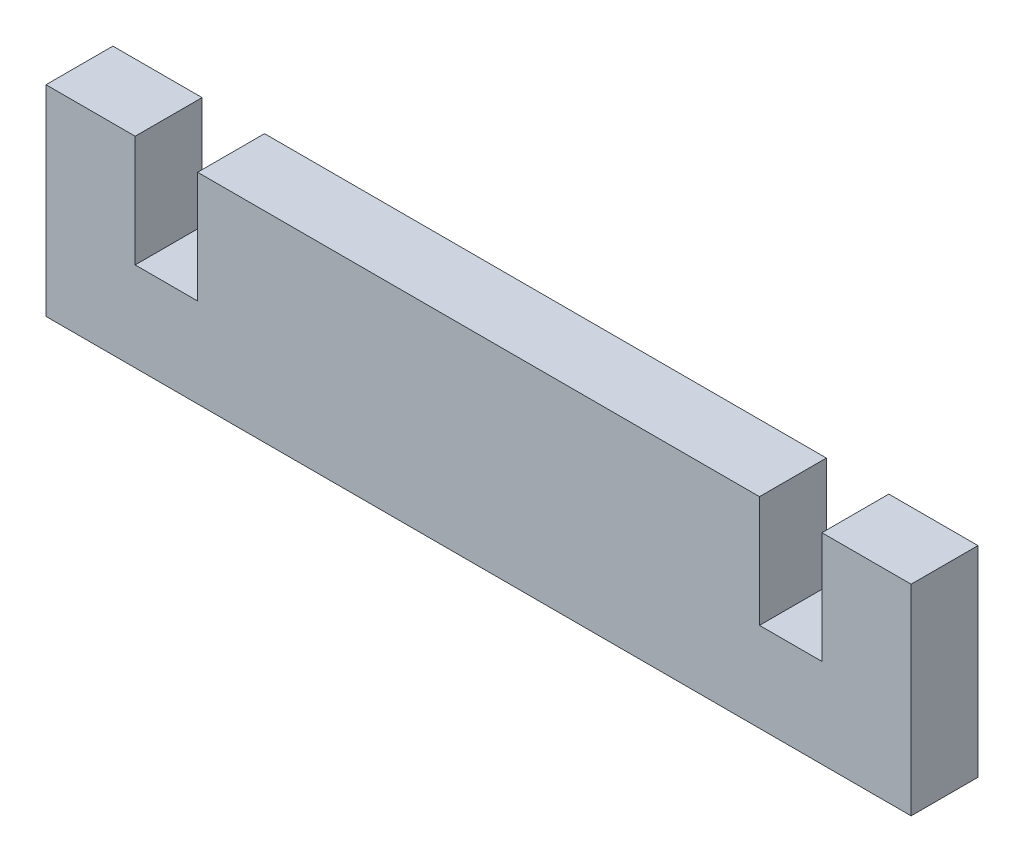
SolidWorks part; units mm, degrees
ref_plane "Plan de face" through (0, 0, 0) normal (0, 0, 1) x (1, 0, 0)
ref_plane "Plan de dessus" through (0, 0, 0) normal (0, 1, 0) x (1, 0, 0)
ref_plane "Plan de droite" through (0, 0, 0) normal (1, 0, 0) x (0, 0, -1)
sketch "Esquisse1" plane through (0, 0, 0) normal (0, 0, 1) x (1, 0, 0)
  line L0 (0, 0) -> (0, 18)
  line L1 (0, 18) -> (8, 18)
  line L2 (8, 18) -> (8, 8)
  line L3 (8, 8) -> (13.6, 8)
  line L4 (13.6, 8) -> (13.6, 18)
  line L5 (13.6, 18) -> (64, 18)
  line L6 (64, 18) -> (64, 8)
  line L7 (64, 8) -> (69.6, 8)
  line L8 (69.6, 8) -> (69.6, 18)
  line L9 (69.6, 18) -> (77.6, 18)
  line L10 (77.6, 18) -> (77.6, 0)
  line L11 (77.6, 0) -> (0, 0)
  dimension "D1" = 50.4
  dimension "D2" = 5.6
  dimension "D3" = 5.6
  dimension "D4" = 10
  dimension "D5" = 8
  dimension "D6" = 8
  dimension "D7" = 8
extrude "Boss.-Extru.1" add sketch "Esquisse1" along normal blind 6
